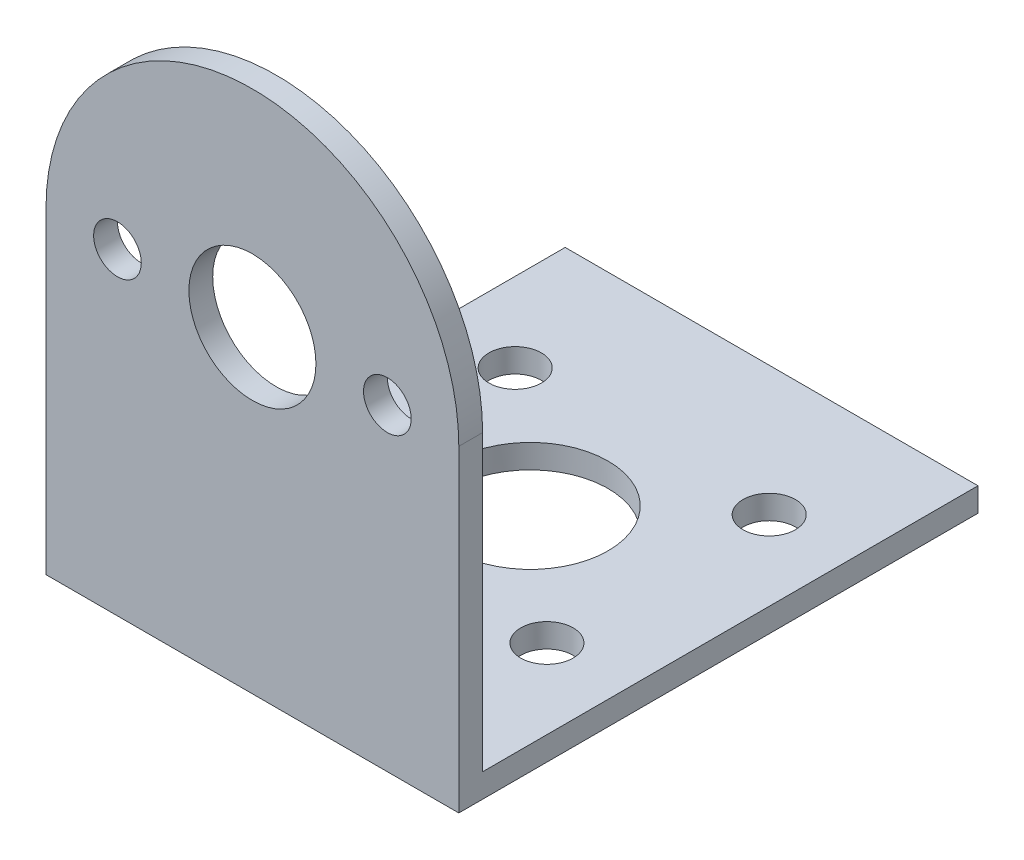
SolidWorks part; units mm, degrees
ref_plane "前视基准面" through (0, 0, 0) normal (0, 0, 1) x (1, 0, 0)
ref_plane "上视基准面" through (0, 0, 0) normal (0, 1, 0) x (1, 0, 0)
ref_plane "右视基准面" through (0, 0, 0) normal (1, 0, 0) x (0, 0, -1)
sketch "草图1" plane through (0, 0, 0) normal (0, 0, 1) x (1, 0, 0)
  line L0 (0, 0) -> (8.5, 0)
  line L1 (0, 0) -> (0, 12.7282) construction
  line L2 (-13, 0) -> (-13, -20)
  line L3 (-13, -20) -> (13, -20)
  line L4 (13, 0) -> (13, -20)
  line L5 (13, -20) -> (13, -16.7)
  circle A0 centre (0, 0) radius 4
  circle A1 centre (8.5, 0) radius 1.5
  circle A2 centre (-8.5, 0) radius 1.5
  arc A3 (13, 0) -> (-13, 0) centre (0, 0) ccw
  circle A4 centre (8.5, 0) radius 3
  circle A5 centre (-8.5, 0) radius 3
  point P8 (0, 13)
  dimension "D1" = 8
  dimension "D3" = 3
  dimension "D4" = 26
  dimension "D6" = 6
  dimension "D7" = 6
  dimension "D2" = 8.5
  dimension "D5" = 33
  dimension "D8" = 3.3
extrude "凸台-拉伸1" add sketch "草图1" along normal blind 3
sketch "草图2" plane through (0, 0, 0) normal (0, 0, -1) x (-1, 0, 0)
  circle A0 centre (8.5, 0) radius 3 construction
  circle A1 centre (8.5, 0) radius 3
  circle A2 centre (-8.5, 0) radius 3 construction
  circle A3 centre (-8.5, 0) radius 3
  circle A4 centre (8.5, 0) radius 1.5
  circle A5 centre (-8.5, 0) radius 1.5
  dimension "D1" = 3
  dimension "D2" = 3
extrude "凸台-拉伸2" add sketch "草图2" against normal blind 1.5
sketch "草图3" plane through (0, -20, 0) normal (0, -1, 0) x (1, 0, 0)
  line L0 (-13, 0) -> (-13, -29.7)
  line L1 (-13, -29.7) -> (13, -29.7)
  line L2 (13, 0) -> (13, -29.7)
  line L3 (-13, 0) -> (13, 0) construction
  line L4 (-13, 0) -> (13, 0)
  line L5 (0, -29.7) -> (0, -14.5)
  line L6 (0, -29.7) -> (-8, -29.7)
  circle A0 centre (0, -14.5) radius 4.9
  circle A1 centre (-8, -21.55) radius 1.65
  circle A2 centre (-8, -7.55) radius 1.65
  circle A3 centre (8, -7.55) radius 1.65
  circle A4 centre (8, -21.55) radius 1.65
  dimension "D3" = 9.8
  dimension "D5" = 3.3
  dimension "D6" = 8.15
  dimension "D7" = 8
  dimension "D4" = 14
  dimension "D8" = 3.3
  dimension "D1" = 29.7
  dimension "D2" = 15.2
extrude "凸台-拉伸3" add sketch "草图3" against normal blind 3.3
sketch "草图5" plane through (0, 0, 1.5) normal (0, 0, 1) x (1, 0, 0)
  circle A0 centre (-8.5, 0) radius 1.5 construction
  circle A1 centre (-8.5, 0) radius 3
  circle A2 centre (-8.5, 0) radius 3
  circle A3 centre (-8.5, 0) radius 1.5
  circle A4 centre (8.5, 0) radius 1.5 construction
  circle A5 centre (8.5, 0) radius 1.5
  circle A6 centre (8.5, 0) radius 3 construction
  circle A7 centre (8.5, 0) radius 3
  dimension "D1" = 0
extrude "凸台-拉伸4" add sketch "草图5" along normal up to surface (1.5 mm away) up to face at (11.5, 0, 3)
sketch "草图6" plane through (0, 0, 0) normal (0, 0, -1) x (-1, 0, 0)
  line L3 (-13, -16.7) -> (13, -16.7)
  line L4 (13, -16.7) -> (13, 0)
  line L5 (-13, 0) -> (-13, -16.7)
  line L6 (-13, -16.7) -> (13, -16.7)
  line L7 (13, -16.7) -> (13, 0)
  line L8 (-13, 0) -> (-13, -16.7)
  circle A0 centre (0, 0) radius 4 construction
  arc A1 (13, 0) -> (-13, 0) centre (0, 0) ccw
  arc A2 (13, 0) -> (-13, 0) centre (0, 0) ccw
  circle A3 centre (0, 0) radius 4
  circle A4 centre (8.5, 0) radius 1.5 construction
  circle A5 centre (8.5, 0) radius 1.5
  circle A6 centre (-8.5, 0) radius 1.5 construction
  circle A7 centre (-8.5, 0) radius 1.5
  dimension "D1" = 0
extrude "切除-拉伸1" cut sketch "草图6" against normal blind 1.8
sketch "草图7" plane through (0, -16.7, 0) normal (0, 1, 0) x (1, 0, 0)
  line L4 (-13, 29.7) -> (-13, -1.8)
  line L5 (-13, -1.8) -> (13, -1.8)
  line L6 (13, -1.8) -> (13, 29.7)
  line L7 (13, 29.7) -> (-13, 29.7)
  line L8 (-13, 29.7) -> (-13, -1.8)
  line L9 (-13, -1.8) -> (13, -1.8)
  line L10 (13, -1.8) -> (13, 29.7)
  line L11 (13, 29.7) -> (-13, 29.7)
  circle A0 centre (0, 14.5) radius 4.9 construction
  circle A1 centre (0, 14.5) radius 4.9
  circle A2 centre (-8, 7.55) radius 1.65 construction
  circle A3 centre (-8, 7.55) radius 1.65
  circle A4 centre (8, 7.55) radius 1.65 construction
  circle A5 centre (8, 7.55) radius 1.65
  circle A6 centre (8, 21.55) radius 1.65 construction
  circle A7 centre (8, 21.55) radius 1.65
  circle A8 centre (-8, 21.55) radius 1.65 construction
  circle A9 centre (-8, 21.55) radius 1.65
  dimension "D1" = 0
extrude "切除-拉伸2" cut sketch "草图7" against normal blind 1.8
sketch "草图11" plane through (0, 0, 1.8) normal (0, 0, -1) x (-1, 0, 0)
  line L3 (-13, 0) -> (-13, -18.5)
  line L4 (-13, -18.5) -> (13, -18.5)
  line L5 (13, -18.5) -> (13, 0)
  line L6 (-13, 0) -> (-13, -18.5)
  line L7 (-13, -18.5) -> (13, -18.5)
  line L8 (13, -18.5) -> (13, 0)
  circle A0 centre (0, 0) radius 4 construction
  arc A1 (13, 0) -> (-13, 0) centre (0, 0) ccw
  arc A2 (13, 0) -> (-13, 0) centre (0, 0) ccw
  circle A3 centre (0, 0) radius 4
  circle A4 centre (-8.5, 0) radius 1.5 construction
  circle A5 centre (-8.5, 0) radius 1.5
  circle A6 centre (8.5, 0) radius 1.5 construction
  circle A7 centre (8.5, 0) radius 1.5
  dimension "D1" = 0
extrude "凸台-拉伸5" add sketch "草图11" along normal blind 0.3
